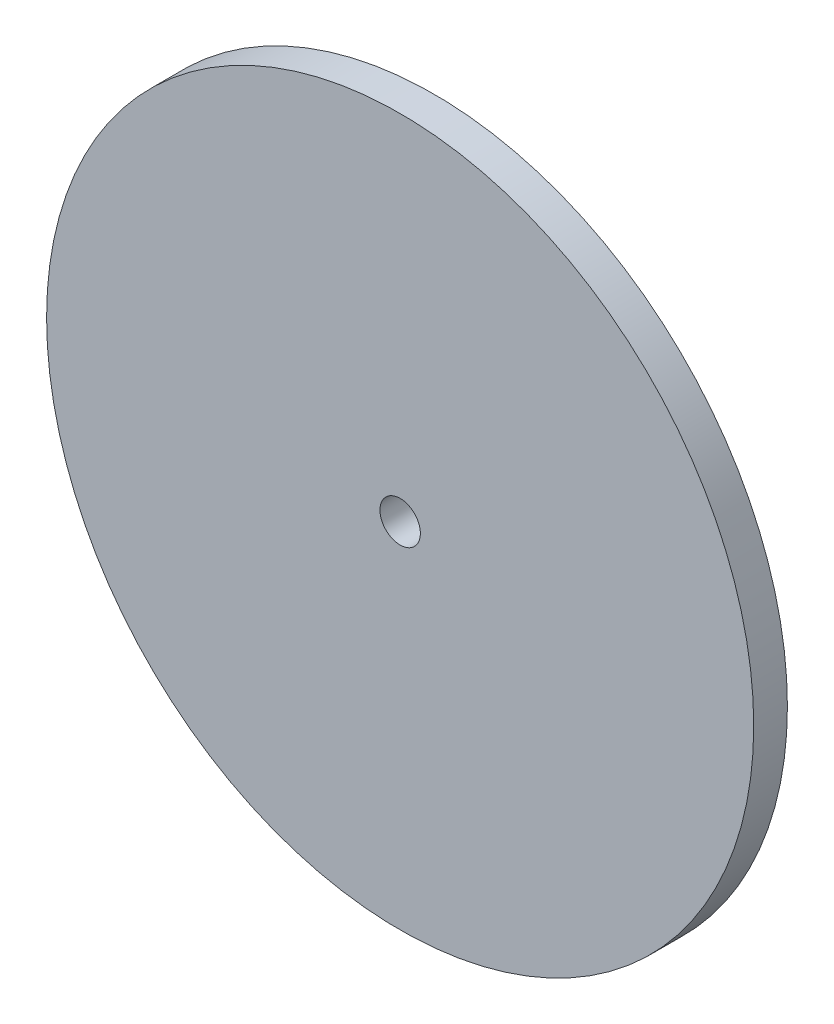
SolidWorks part; units mm, degrees
ref_plane "Ön Düzlem" through (0, 0, 0) normal (0, 0, 1) x (1, 0, 0)
ref_plane "Üst Düzlem" through (0, 0, 0) normal (0, 1, 0) x (1, 0, 0)
ref_plane "Sağ Düzlem" through (0, 0, 0) normal (1, 0, 0) x (0, 0, -1)
sketch "Çizim1" plane through (0, 0, 0) normal (0, 0, 1) x (1, 0, 0)
  circle A0 centre (0, 0) radius 8
  circle A1 centre (0, 0) radius 3
extrude "Yükseklik-Ekstrüzyon1" add sketch "Çizim1" along normal blind 11.1
sketch "Çizim2" plane through (0, 0, 11.1) normal (0, 0, 1) x (1, 0, 0)
  circle A0 centre (0, 0) radius 52.5
  circle A1 centre (0, 0) radius 3
extrude "Yükseklik-Ekstrüzyon2" add sketch "Çizim2" against normal blind 5
